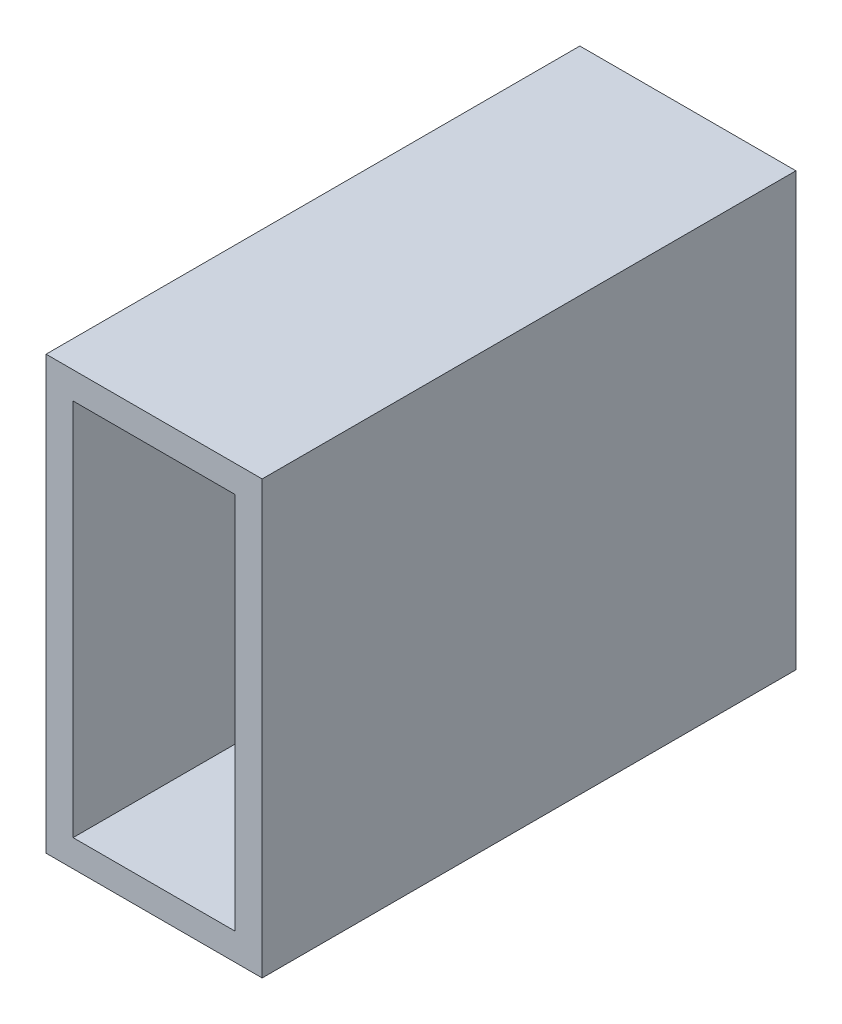
SolidWorks part; units mm, degrees
material "6061-T6 (SS)"
ref_plane "Front Plane" through (0, 0, 0) normal (0, 0, 1) x (1, 0, 0)
ref_plane "Top Plane" through (0, 0, 0) normal (0, 1, 0) x (1, 0, 0)
ref_plane "Right Plane" through (0, 0, 0) normal (1, 0, 0) x (0, 0, -1)
sketch "Sketch1" plane through (0, 0, 0) normal (0, 0, 1) x (1, 0, 0)
  line L1 (-12.7, -25.4) -> (12.7, -25.4)
  line L2 (-12.7, -25.4) -> (-12.7, 25.4)
  line L3 (-12.7, 25.4) -> (12.7, 25.4)
  line L4 (12.7, -25.4) -> (12.7, 25.4)
  line L5 (0, 25.4) -> (0, -25.4) construction
  line L6 (-12.7, 0) -> (12.7, 0) construction
  line L7 (-9.525, -22.225) -> (9.525, -22.225)
  line L8 (-9.525, -22.225) -> (-9.525, 22.225)
  line L9 (-9.525, 22.225) -> (9.525, 22.225)
  line L10 (9.525, -22.225) -> (9.525, 22.225)
  line L11 (0, 22.225) -> (0, -22.225) construction
  line L12 (-9.525, 0) -> (9.525, 0) construction
  point P0 (0, 0)
  point P4 (0, 0)
  dimension "D1" = 25.4
  dimension "D2" = 50.8
  dimension "D3" = 3.175
  dimension "D4" = 3.175
extrude "Boss-Extrude1" add sketch "Sketch1" along normal mid plane 62.738
